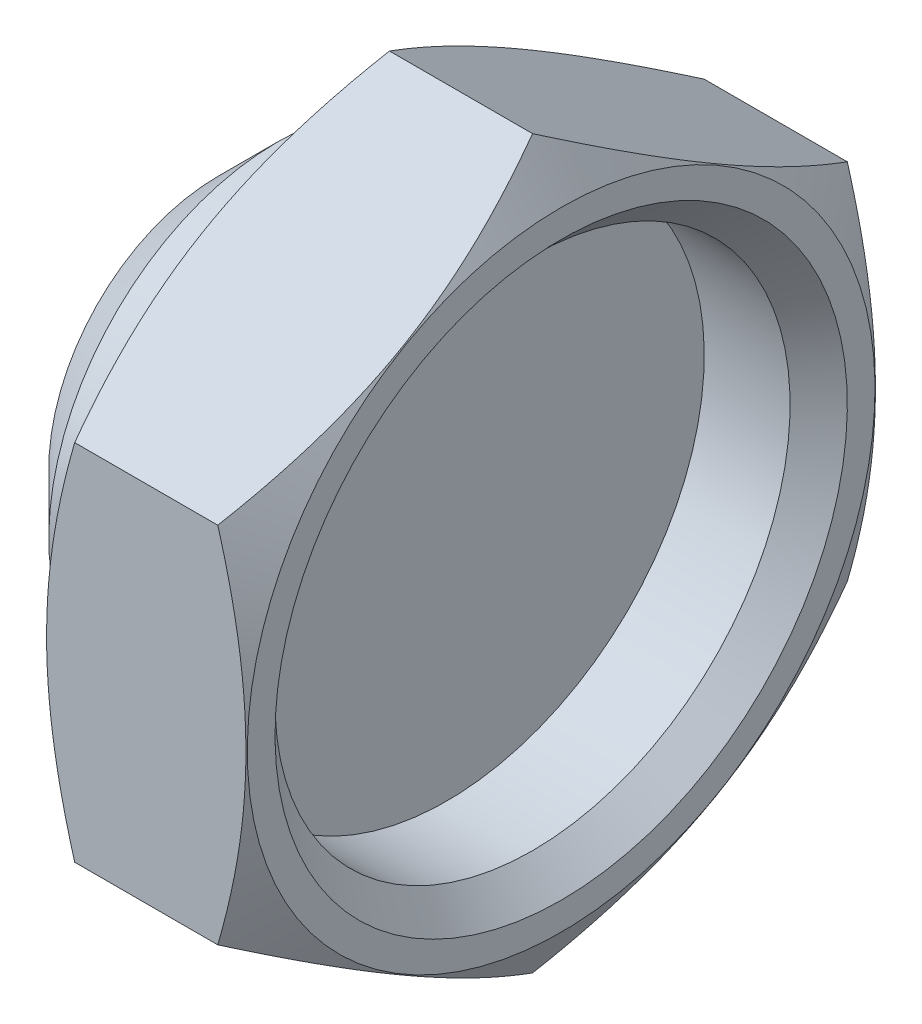
SolidWorks part; units mm, degrees
ref_plane "Спереди" through (0, 0, 0) normal (0, 0, 1) x (1, 0, 0)
ref_plane "Сверху" through (0, 0, 0) normal (0, 1, 0) x (1, 0, 0)
ref_plane "Справа" through (0, 0, 0) normal (1, 0, 0) x (0, 0, -1)
sketch "Эскиз1" plane through (0, 0, 0) normal (0, 0, 1) x (1, 0, 0)
  line L0 (0, 0) -> (-6, 0)
  line L1 (-6, 0) -> (-6, -2.9524)
  line L2 (-6, -2.9524) -> (-4.9524, -4)
  line L3 (-4.9524, -4) -> (-3.5, -4)
  line L4 (-3.5, -4) -> (-3.5, -5.484)
  line L5 (-3, -6.35) -> (-0.5, -6.35)
  line L6 (0, -5.484) -> (0, 0)
  line L7 (0, -5.484) -> (-0.5, -6.35)
  line L8 (-3.5, -5.484) -> (-3, -6.35)
  dimension "D1" = 4
  dimension "D2" = 45
  dimension "D3" = 6
  dimension "D4" = 3.5
  dimension "D5" = 6.35
  dimension "D6" = 30
  dimension "D8" = 30
revolve "Повернуть1" add sketch "Эскиз1" angle 360 about L0
sketch "Эскиз2" plane through (0, 0, 0) normal (1, 0, 0) x (0, 0, -1)
  line L1 (0, 6.35) -> (-5.4993, 3.175)
  line L2 (-5.4993, 3.175) -> (-5.4993, -3.175)
  line L3 (-5.4993, -3.175) -> (0, -6.35)
  line L4 (0, -6.35) -> (5.4993, -3.175)
  line L5 (5.4993, -3.175) -> (5.4993, 3.175)
  line L6 (5.4993, 3.175) -> (0, 6.35)
  circle A0 centre (0, 0) radius 5.4993 construction
  circle A1 centre (0, 0) radius 6.35
extrude "Вырез-Вытянуть1" cut sketch "Эскиз2" against normal blind 10
sketch "Эскиз3" plane through (0, 0, 0) normal (1, 0, 0) x (0, 0, -1)
  circle A0 centre (0, 0) radius 4.5
  dimension "D1" = 9
extrude "Вырез-Вытянуть2" cut sketch "Эскиз3" against normal blind 2
chamfer "Фаска1" distance 0.5 angle 45 1 edges at (0, 4.5, 0)
